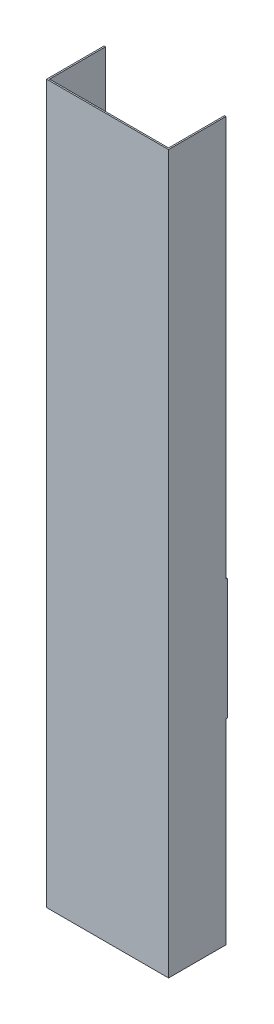
SolidWorks part; units mm, degrees
material "AISI 304"
ref_plane "Front Plane" through (0, 0, 0) normal (0, 0, 1) x (1, 0, 0)
ref_plane "Top Plane" through (0, 0, 0) normal (0, 1, 0) x (1, 0, 0)
ref_plane "Right Plane" through (0, 0, 0) normal (1, 0, 0) x (0, 0, -1)
sketch "Sketch1" plane through (0, 0, 0) normal (0, 1, 0) x (1, 0, 0)
  line L0 (0, 0) -> (0, -40)
  line L1 (0, -40) -> (85, -40)
  line L2 (85, -40) -> (85, 0)
  line L3 (1, 0) -> (1, -39)
  line L4 (1, -39) -> (84, -39)
  line L5 (84, -39) -> (84, 0)
  line L6 (85, 0) -> (84, 0)
  line L7 (1, 0) -> (0, 0)
  dimension "D1" = 40
  dimension "D2" = 85
  dimension "D3" = 1
extrude "Boss-Extrude1" add sketch "Sketch1" along normal blind 500
sketch "Sketch2" plane through (0, 0, 0) normal (0, 0, -1) x (-1, 0, 0)
  line L0 (-85, 500) -> (-85, 0) construction
  line L1 (-85, 220.6956) -> (0, 220.6956)
  line L2 (-85, 220.6956) -> (-85, 136.4818)
  line L3 (-85, 136.4818) -> (0, 136.4818)
  line L4 (0, 220.6956) -> (0, 136.4818)
  line L5 (-85, 220.6956) -> (0, 136.4818) construction
  line L6 (-85, 136.4818) -> (0, 220.6956) construction
  line L7 (0, 500) -> (0, 0) construction
  point P4 (-42.5, 178.5887)
extrude "Boss-Extrude2" add sketch "Sketch2" along normal blind 1
